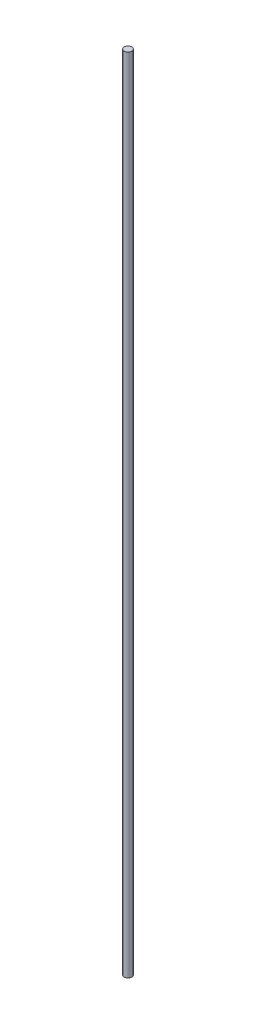
SolidWorks part; units mm, degrees
ref_plane "Front" through (0, 0, 0) normal (0, 0, 1) x (1, 0, 0)
ref_plane "Top" through (0, 0, 0) normal (0, 1, 0) x (1, 0, 0)
ref_plane "Right" through (0, 0, 0) normal (1, 0, 0) x (0, 0, -1)
sketch "Эскиз1" plane through (0, 0, 0) normal (0, 1, 0) x (1, 0, 0)
  circle A0 centre (0, 0) radius 1.59
extrude "Бобышка-Вытянуть1" add sketch "Эскиз1" along normal blind 340.5
